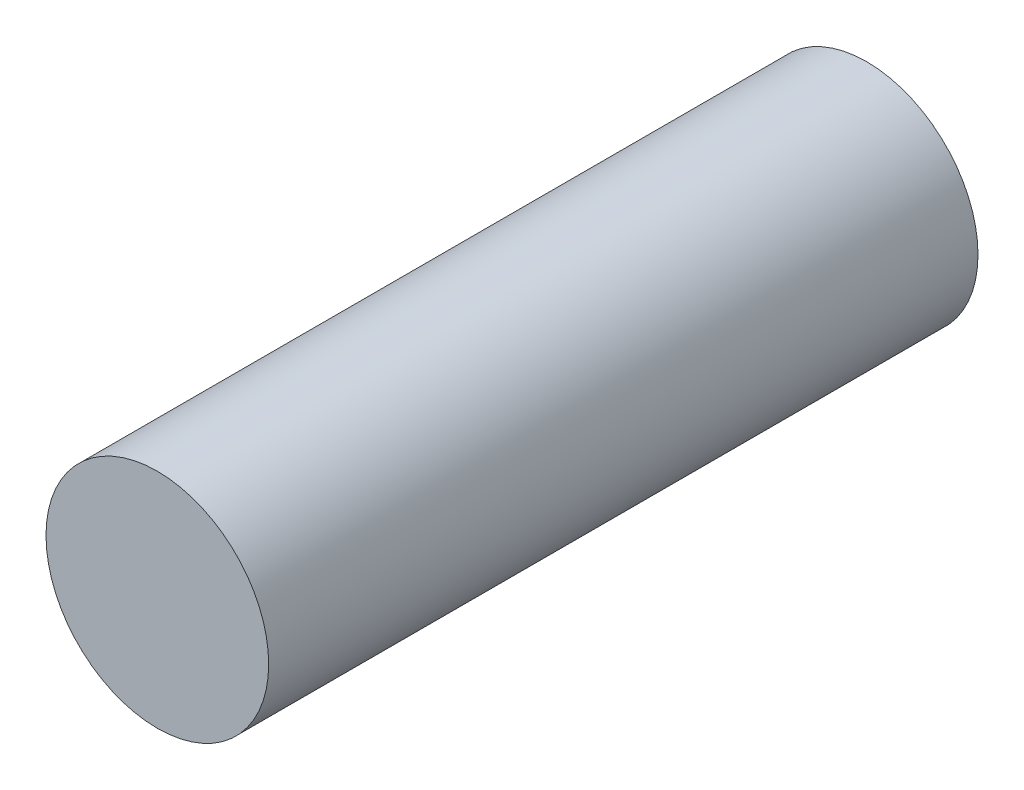
SolidWorks part; units mm, degrees
ref_plane "Front Plane" through (0, 0, 0) normal (0, 0, 1) x (1, 0, 0)
ref_plane "Top Plane" through (0, 0, 0) normal (0, 1, 0) x (1, 0, 0)
ref_plane "Right Plane" through (0, 0, 0) normal (1, 0, 0) x (0, 0, -1)
sketch "Sketch1" plane through (0, 0, 0) normal (0, 0, 1) x (1, 0, 0)
  circle A0 centre (12.0117, -12.4904) radius 15.9477
extrude "Boss-Extrude1" add sketch "Sketch1" along normal blind 101.6
